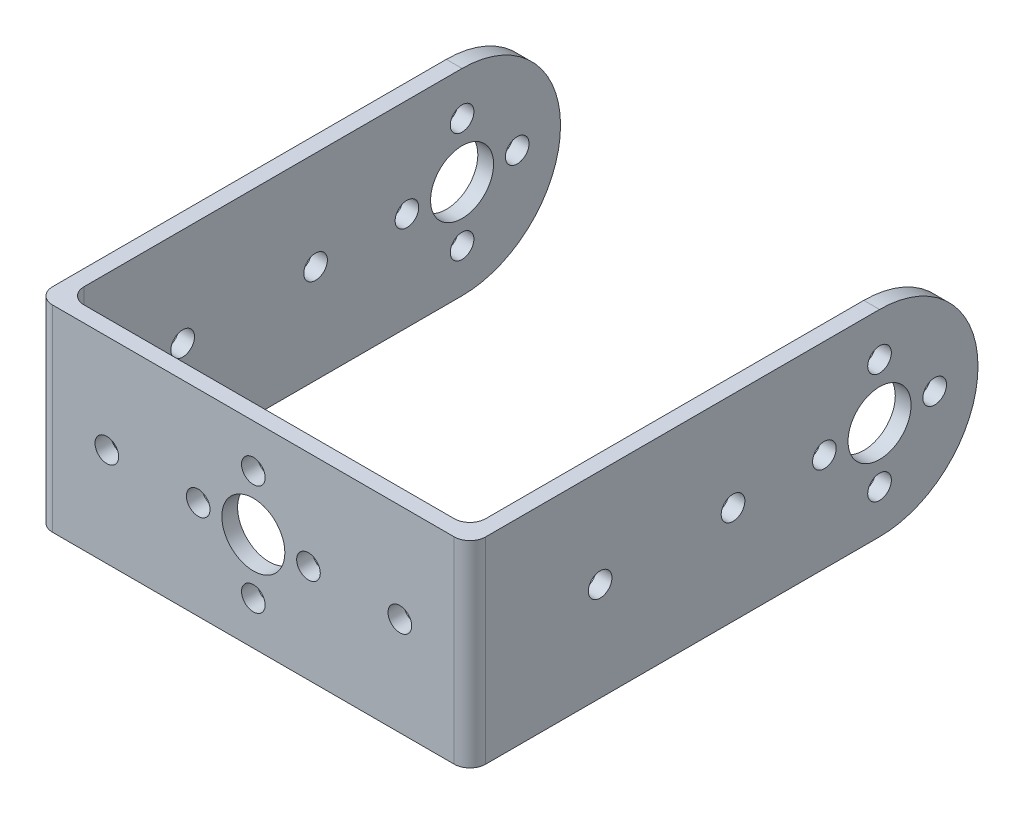
SolidWorks part; units mm, degrees
ref_plane "前视基准面" through (0, 0, 0) normal (0, 0, 1) x (1, 0, 0)
ref_plane "上视基准面" through (0, 0, 0) normal (0, 1, 0) x (1, 0, 0)
ref_plane "右视基准面" through (0, 0, 0) normal (1, 0, 0) x (0, 0, -1)
sketch "草图1" plane through (0, 0, 0) normal (0, 1, 0) x (1, 0, 0)
  line L0 (0, 0) -> (0, 50.4207) construction
  line L1 (0, 0) -> (27.5, 0)
  line L2 (27.5, 0) -> (27.5, 64.5)
  line L3 (27.5, 64.5) -> (25.5, 64.5)
  line L4 (25.5, 64.5) -> (25.5, 2)
  line L5 (25.5, 2) -> (0, 2)
  line L6 (0, 2) -> (0, 0)
  dimension "D1" = 51
  dimension "D2" = 62.5
  dimension "D3" = 2
  dimension "D4" = 2
extrude "凸台-拉伸1" add sketch "草图1" along normal blind 25
sketch "草图2" plane through (27.5, 0, 0) normal (1, 0, 0) x (0, 0, -1)
  line L0 (0, 12.5) -> (64.5, 12.5) construction
  line L1 (0, 25) -> (0, 0) construction
  line L2 (64.5, 25) -> (64.5, 0) construction
  line L3 (0, 25) -> (64.5, 25) construction
  line L4 (0, 0) -> (64.5, 0) construction
  circle A0 centre (16.53, 12.5) radius 1.5
  circle A1 centre (52, 12.5) radius 7 construction
  circle A2 centre (52, 19.5) radius 1.5
  circle A3 centre (59, 12.5) radius 1.5
  circle A4 centre (52, 5.5) radius 1.5
  circle A5 centre (45, 12.5) radius 1.5
  circle A6 centre (33.4, 12.5) radius 1.5
  circle A7 centre (52, 12.5) radius 4
  arc A8 (52, 25) -> (52, 0) centre (52, 12.5) cw
  line M8 (0, 0) -> (64.5, 0)
  line M9 (64.5, 0) -> (64.5, 25)
  line M10 (64.5, 25) -> (0, 25)
  dimension "D1" = 14
  dimension "D2" = 3
  dimension "D5" = 8
  dimension "D6" = 12.5
  dimension "D3" = 16.87
  dimension "D4" = 18.6
extrude "切除-拉伸1" cut sketch "草图2" against normal blind 25 contours A0 | A5 | A7 | A2 | A3 | A4 | A8 M10 M9 | A8 M9 M8 | A6
mirror "镜向1" about plane through (0, 25, -2) normal (1, 0, 0) of "切除-拉伸1", "凸台-拉伸1"
sketch "草图3" plane through (0, 0, 0) normal (0, 0, 1) x (1, 0, 0)
  line L0 (0, 0) -> (0, 25) construction
  line L1 (-27.5, 25) -> (27.5, 25) construction
  line L2 (-27.5, 12.5) -> (27.5, 12.5) construction
  line L3 (-27.5, 25) -> (-27.5, 0) construction
  line L4 (27.5, 25) -> (27.5, 0) construction
  circle A0 centre (0, 12.5) radius 7 construction
  circle A1 centre (7, 12.5) radius 1.5
  circle A2 centre (0, 19.5) radius 1.5
  circle A3 centre (-7, 12.5) radius 1.5
  circle A4 centre (0, 5.5) radius 1.5
  circle A5 centre (18.6, 12.5) radius 1.5
  circle A6 centre (-18.6, 12.5) radius 1.5
  circle A7 centre (0, 12.5) radius 4
  dimension "D1" = 14
  dimension "D2" = 3
  dimension "D5" = 8
  dimension "D3" = 18.6
  dimension "D4" = 18.6
extrude "切除-拉伸2" cut sketch "草图3" against normal blind 25
fillet "圆角1" radius 2 4 edges at (25.5, 12.5, -2) (-25.5, 12.5, -2) (27.5, 12.5, 0) (-27.5, 12.5, 0)
